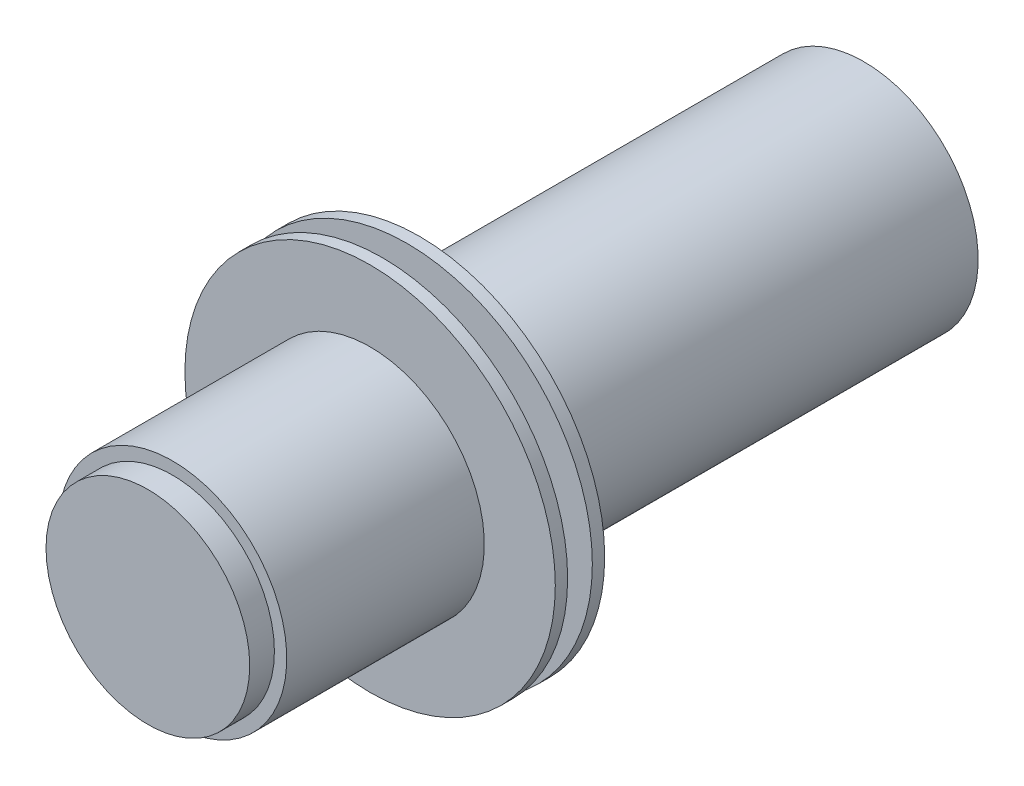
SolidWorks part; units mm, degrees
ref_plane "Front Plane" through (0, 0, 0) normal (0, 0, 1) x (1, 0, 0)
ref_plane "Top Plane" through (0, 0, 0) normal (0, 1, 0) x (1, 0, 0)
ref_plane "Right Plane" through (0, 0, 0) normal (1, 0, 0) x (0, 0, -1)
sketch "Sketch1" plane through (0, 0, 0) normal (0, 0, 1) x (1, 0, 0)
  circle A0 centre (0, 0) radius 9.25
  dimension "D1" = 18.5
extrude "Boss-Extrude1" add sketch "Sketch1" along normal blind 58
sketch "Sketch2" plane through (0, 0, 58) normal (0, 0, 1) x (1, 0, 0)
  circle A0 centre (0, 0) radius 9.25 construction
  circle A1 centre (0, 0) radius 9.25
  circle A2 centre (0, 0) radius 8.25
  dimension "D1" = 1
extrude "Cut-Extrude1" cut sketch "Sketch2" against normal blind 2
ref_plane "Plane1" through (0, 0, 36) normal (0, 0, 1) x (1, 0, 0)
sketch "Sketch3" plane through (0, 0, 36) normal (0, 0, 1) x (1, 0, 0)
  circle A0 centre (0, 0) radius 15
  circle A1 centre (0, 0) radius 9.25 construction
  circle A2 centre (0, 0) radius 9.25
  dimension "D1" = 30
extrude "Boss-Extrude2" add sketch "Sketch3" along normal blind 1 contours A0
pattern_linear "LPattern1" count 2 spacing 3 along (0, 0, 1) of "Boss-Extrude2"
